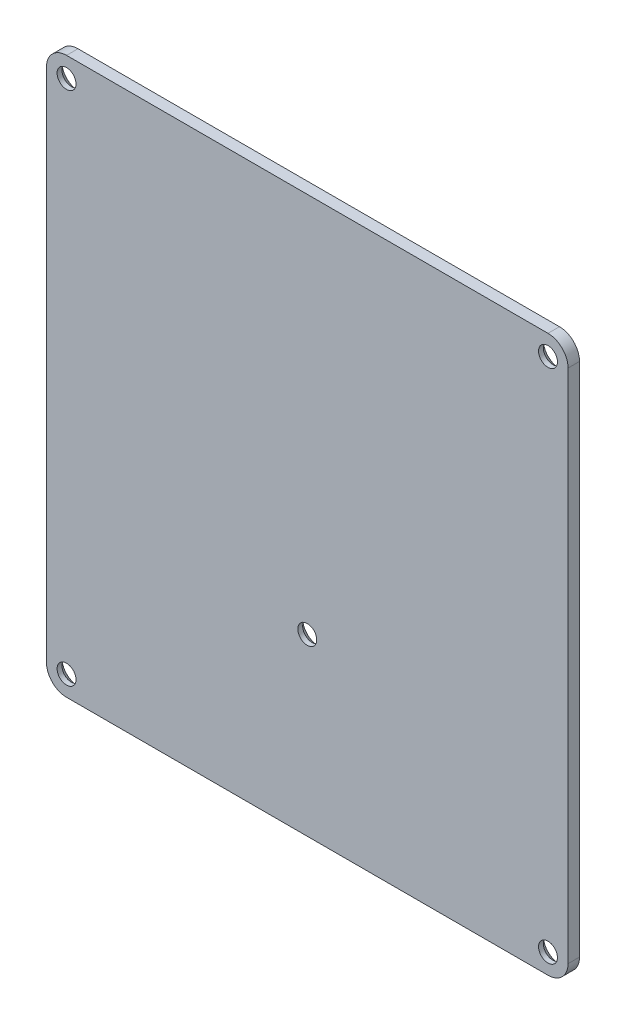
SolidWorks part; units mm, degrees
ref_plane "前视基准面" through (0, 0, 0) normal (0, 0, 1) x (1, 0, 0)
ref_plane "上视基准面" through (0, 0, 0) normal (0, 1, 0) x (1, 0, 0)
ref_plane "右视基准面" through (0, 0, 0) normal (1, 0, 0) x (0, 0, -1)
sketch "草图1" plane through (0, 0, 0) normal (0, 0, 1) x (1, 0, 0)
  line L1 (-42, 48.5) -> (42, 48.5)
  line L2 (-45.5, 45) -> (-45.5, -45)
  line L3 (-42, -48.5) -> (42, -48.5)
  line L4 (45.5, 45) -> (45.5, -45)
  line L5 (-45.5, 48.5) -> (45.5, -48.5) construction
  line L6 (-45.5, -48.5) -> (45.5, 48.5) construction
  arc A0 (-45.5, -45) -> (-42, -48.5) centre (-42, -45) ccw
  arc A1 (42, -48.5) -> (45.5, -45) centre (42, -45) ccw
  arc A2 (42, 48.5) -> (45.5, 45) centre (42, 45) cw
  arc A3 (-42, 48.5) -> (-45.5, 45) centre (-42, 45) ccw
  point P0 (0, 0)
  dimension "D3" = 3.5
  dimension "D1" = 97
  dimension "D2" = 91
extrude "凸台-拉伸1" add sketch "草图1" against normal blind 2
hole_wizard "打孔尺寸开槽半沉头螺钉的类型2" positions "3D草图2" profile "草图3" countersink size "M3" standard "GB"
sketch3d "3D草图2"
  line L0 (42, 45, -2) -> (42, 45, 0) construction
  line L1 (-42, 45, -2) -> (-42, 45, 0) construction
  line L2 (-42, -45, -2) -> (-42, -45, 0) construction
  line L3 (42, -45, -2) -> (42, -45, 0) construction
  point P0 (42, 45, -2)
  point P4 (-42, 45, -2)
  point P8 (-42, -45, -2)
  point P12 (42, -45, -2)
sketch "草图3" plane through (42, 45, -2) normal (1, 0, 0) x (0, 1, 0)
  line L0 (0, 0) -> (0, 15.9914)
  line L1 (0, 15.9914) -> (1.65, 15)
  line L2 (1.65, 15) -> (1.65, 1.15)
  line L3 (1.65, 1.15) -> (2.8, 0)
  line L5 (2.8, 0) -> (0, 0)
  line L6 (-1.65, 1.15) -> (-2.8, 0) construction
  line L10 (0, 15.9914) -> (-1.65, 15) construction
  line L11 (0, -6.35) -> (0, 107.95) construction
  dimension "孔直径" = 3.3
  dimension "孔深度" = 15
  dimension "近端锥形沉头孔直径" = 5.6
  dimension "近端锥形沉头孔角度" = 90
  dimension "导头角度" = 118
sketch "草图5" plane through (0, 0, -2) normal (0, 0, -1) x (-1, 0, 0)
  line L0 (0, 0) -> (0, 43.5111) construction
  line L1 (-19.7913, 30.8517) -> (19.9919, 30.8517) construction
  text T0 "Ruige"
extrude "凸台-拉伸3" add sketch "草图5" along normal blind 0.2
sketch "草图6" plane through (0, 0, -2) normal (0, 0, -1) x (-1, 0, 0)
  line L0 (0, 49.6356) -> (0, -18.6476) construction
hole_wizard "打孔尺寸开槽半沉头螺钉的类型3" positions "3D草图3" profile "草图7" countersink size "M3" standard "GB"
sketch3d "3D草图3"
  line L0 (0, 49.6356, -2) -> (0, -18.6476, -2) construction
  line L1 (42, 48.5, -2) -> (-42, 48.5, -2) construction
  point P0 (0, -18, -2)
  dimension "D1" = 66.5
sketch "草图7" plane through (0, -18, -2) normal (1, 0, 0) x (0, 1, 0)
  line L0 (0, 0) -> (0, 15.9914)
  line L1 (0, 15.9914) -> (1.65, 15)
  line L2 (1.65, 15) -> (1.65, 1.15)
  line L3 (1.65, 1.15) -> (2.8, 0)
  line L5 (2.8, 0) -> (0, 0)
  line L6 (-1.65, 1.15) -> (-2.8, 0) construction
  line L10 (0, 15.9914) -> (-1.65, 15) construction
  line L11 (0, -6.35) -> (0, 107.95) construction
  dimension "孔直径" = 3.3
  dimension "孔深度" = 15
  dimension "近端锥形沉头孔直径" = 5.6
  dimension "近端锥形沉头孔角度" = 90
  dimension "导头角度" = 118
